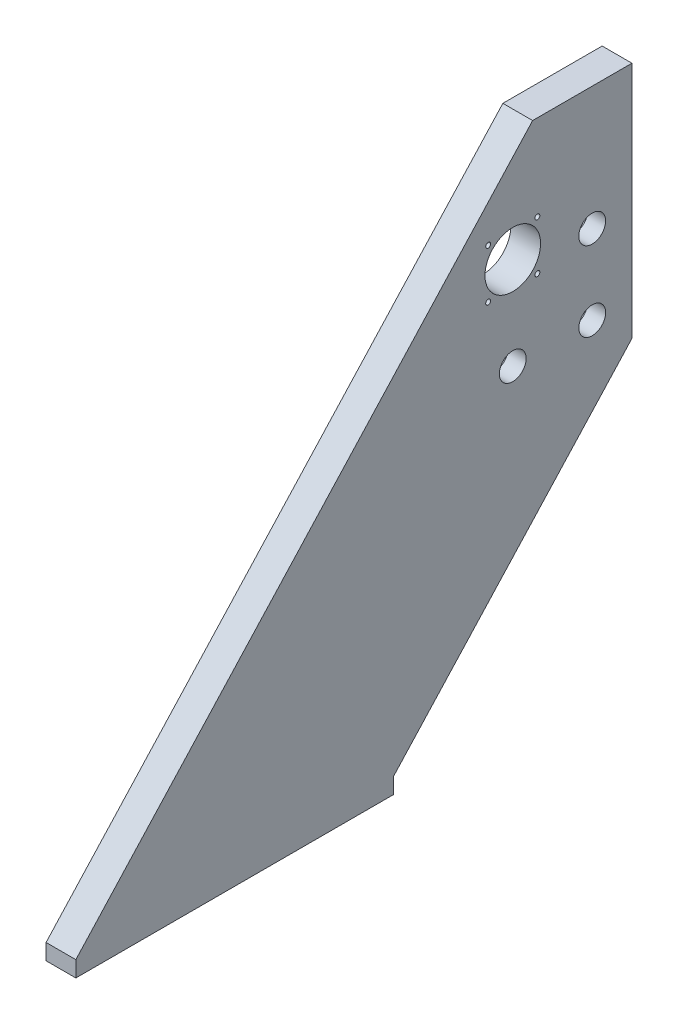
SolidWorks part; units mm, degrees
material "3.1355 (EN-AW 2024)"
ref_plane "Спереди" through (0, 0, 0) normal (0, 0, 1) x (1, 0, 0)
ref_plane "Сверху" through (0, 0, 0) normal (0, 1, 0) x (1, 0, 0)
ref_plane "Справа" through (0, 0, 0) normal (1, 0, 0) x (0, 0, -1)
sketch "Эскиз1" plane through (0, 0, 0) normal (1, 0, 0) x (0, 0, -1)
  line L0 (-80, 0) -> (0, 0)
  line L1 (0, 0) -> (80, 0)
  line L2 (80, 0) -> (80, 8)
  line L5 (200, 258.9091) -> (150, 258.9091)
  line L7 (150, 258.9091) -> (-80, 8)
  line L9 (-80, 8) -> (-80, 0)
  line L10 (80, 8) -> (200, 138.9091)
  line L11 (200, 138.9091) -> (200, 258.9091)
  dimension "D1" = 160
  dimension "D2" = 120
  dimension "D3" = 8
  dimension "D4" = 50
  dimension "D6" = 8
  dimension "D7" = 120
extrude "База" add sketch "Эскиз1" along normal mid plane 15
hole_wizard "Крепление к плите M8" positions "Эскиз2" profile "Эскиз3" tap size "M8" standard "DIN"
sketch "Эскиз2" plane through (0, 0, 0) normal (0, -1, 0) x (-1, 0, 0)
  line L6 (0, 50) -> (0, 0) construction
  line L7 (0, 0) -> (0, -50) construction
  point P3 (0, -50)
  point P5 (0, 50)
  dimension "D1" = 100
sketch "Эскиз3" plane through (0, 0, 50) normal (1, 0, 0) x (0, 0, -1)
  line L0 (0, 0) -> (0, 32.0429)
  line L1 (0, 32.0429) -> (3.4, 30)
  line L2 (3.4, 30) -> (3.4, 0)
  line L5 (3.4, 0) -> (0, 0)
  line L10 (0, 32.0429) -> (-3.4, 30) construction
  line L11 (0, -6.35) -> (0, 107.95) construction
  dimension "Диаметр сверла" = 6.8
  dimension "Глубина сверла" = 30
  dimension "Угол заточки сверла" = 118
cosmetic thread "Отверстие резьбы1" parameters "D1"=25, "D2"=8
cosmetic thread "Отверстие резьбы2" parameters "D1"=25, "D2"=8
hole_wizard "К профилю M12" positions "Эскиз8" profile "Эскиз9" counterbore size "M12" standard "DIN" end condition through all
sketch "Эскиз8" plane through (-7.5, 0, 0) normal (1, 0, 0) x (0, 0, -1)
  line L2 (200, 138.9091) -> (200, 258.9091) construction
  line L3 (200, 258.9091) -> (150, 258.9091) construction
  point P0 (180, 196.8091)
  point P2 (180, 156.8091)
  point P11 (140, 156.8091)
  dimension "D1" = 40
  dimension "D2" = 62.1
  dimension "D3" = 20
  dimension "D4" = 40
sketch "Эскиз9" plane through (-7.5, 196.8091, -180) normal (0, 1, 0) x (0, 0, 1)
  line L0 (0, 0) -> (0, 15)
  line L1 (0, 15) -> (6.75, 15)
  line L3 (6.75, 15) -> (6.75, 6)
  line L4 (10, 6) -> (6.75, 6)
  line L5 (10, 6) -> (10, 0.025)
  line L6 (10, 0.025) -> (10.025, 0)
  line L7 (10.025, 0) -> (0, 0)
  line L8 (-10, 0.025) -> (-10.025, 0) construction
  line L11 (0, -6.35) -> (0, 107.95) construction
  dimension "Диаметр сквозного отверстия" = 13.5
  dimension "Глубина сквозного отверстия" = 15
  dimension "Диаметр цековки" = 20
  dimension "Глубина цековки" = 6
  dimension "Диаметр передней зенковки" = 20.05
  dimension "Угол передней зенковки" = 90
sketch "Эскиз12" plane through (-7.5, 0, 0) normal (-1, 0, 0) x (0, 0, 1)
  line L0 (-200, 138.9091) -> (-200, 258.9091) construction
  circle A0 centre (-140, 203.31) radius 14
  dimension "D3" = 28
  dimension "D1" = 60
  dimension "D2" = 203.31
extrude "Вырез-Вытянуть1" cut sketch "Эскиз12" against normal through all
sketch "Эскиз14" plane through (-7.5, 0, 0) normal (-1, 0, 0) x (0, 0, 1)
  line L1 (-152.3744, 190.9356) -> (-127.6256, 190.9356)
  line L2 (-152.3744, 190.9356) -> (-152.3744, 215.6844)
  line L3 (-152.3744, 215.6844) -> (-127.6256, 215.6844)
  line L4 (-127.6256, 190.9356) -> (-127.6256, 215.6844)
  line L5 (-152.3744, 190.9356) -> (-127.6256, 215.6844) construction
  line L6 (-152.3744, 215.6844) -> (-127.6256, 190.9356) construction
  circle A1 centre (-127.6256, 215.6844) radius 1
  circle A2 centre (-127.6256, 190.9356) radius 1
  circle A3 centre (-152.3744, 190.9356) radius 1
  circle A4 centre (-152.3744, 215.6844) radius 1
  point P0 (-140, 203.31)
  dimension "D1" = 35
  dimension "D2" = 2
hole_wizard "FF10-M3" positions "Эскиз17" profile "Эскиз18" tap size "M3" standard "DIN" end condition through all
sketch "Эскиз17" plane through (-7.5, 0, 0) normal (-1, 0, 0) x (0, 0, 1)
  point P0 (-127.6256, 215.6844)
  point P3 (-127.6256, 190.9356)
  point P6 (-152.3744, 190.9356)
  point P9 (-152.3744, 215.6844)
sketch "Эскиз18" plane through (-7.5, 215.6844, -127.6256) normal (0, 1, 0) x (0, 0, 1)
  line L0 (0, 0) -> (0, 15)
  line L1 (0, 15) -> (1.25, 15)
  line L2 (1.25, 15) -> (1.25, 0.275)
  line L3 (1.25, 0.275) -> (1.525, 0)
  line L5 (1.525, 0) -> (0, 0)
  line L6 (-1.25, 0.275) -> (-1.525, 0) construction
  line L11 (0, -6.35) -> (0, 107.95) construction
  dimension "Диаметр проходного сверла" = 2.5
  dimension "Глубина проходного сверла" = 15
  dimension "Диаметр передней зенковки" = 3.05
  dimension "Угол передней зенковки" = 90
cosmetic thread "Отверстие резьбы7" parameters "D2"=3
cosmetic thread "Отверстие резьбы8" parameters "D2"=3
cosmetic thread "Отверстие резьбы9" parameters "D2"=3
cosmetic thread "Отверстие резьбы10" parameters "D2"=3
